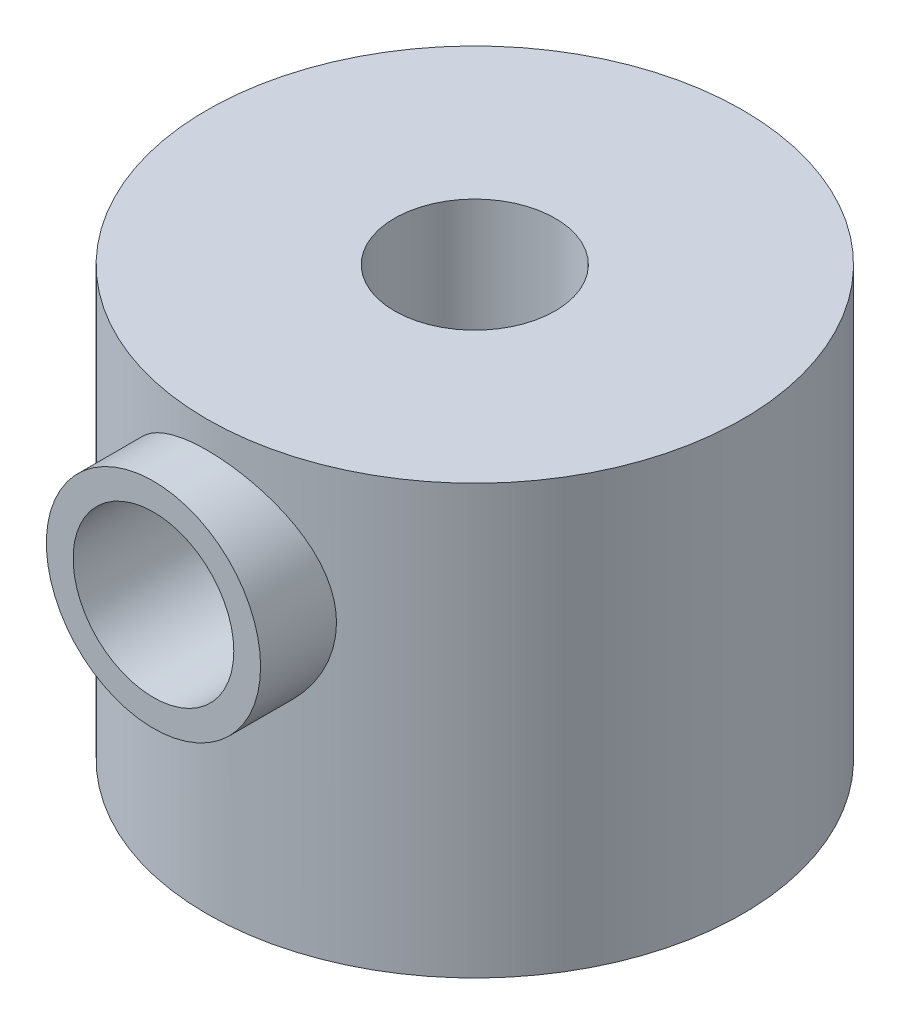
SolidWorks part; units mm, degrees
ref_plane "Front Plane" through (0, 0, 0) normal (0, 0, 1) x (1, 0, 0)
ref_plane "Top Plane" through (0, 0, 0) normal (0, 1, 0) x (1, 0, 0)
ref_plane "Right Plane" through (0, 0, 0) normal (1, 0, 0) x (0, 0, -1)
sketch "Sketch1" plane through (0, 0, 0) normal (0, 1, 0) x (1, 0, 0)
  circle A0 centre (0, 0) radius 5
  circle A1 centre (0, 0) radius 1.5
  dimension "D1" = 3
  dimension "D2" = 10
extrude "Boss-Extrude1" add sketch "Sketch1" along normal blind 8
ref_plane "Plane1" through (0, 0, 6) normal (0, 0, 1) x (1, 0, 0)
sketch "Sketch6" plane through (0, 0, 6) normal (0, 0, 1) x (1, 0, 0)
  line L0 (-5, 4) -> (5, 4) construction
  line L1 (-5, 8) -> (-5, 0) construction
  line L2 (5, 0) -> (5, 8) construction
  line L3 (-5, 5.5) -> (5, 5.5) construction
  circle A0 centre (0, 5.5) radius 2
  dimension "D2" = 4
  dimension "D1" = 1.5
extrude "Boss-Extrude4" add sketch "Sketch6" against normal blind 3.5
sketch "Sketch7" plane through (0, 0, 6) normal (0, 0, 1) x (1, 0, 0)
  circle A0 centre (0, 5.5) radius 1.5
  dimension "D1" = 3
extrude "Cut-Extrude3" cut sketch "Sketch7" against normal up to surface (6 mm away) up to plane "Front Plane"
